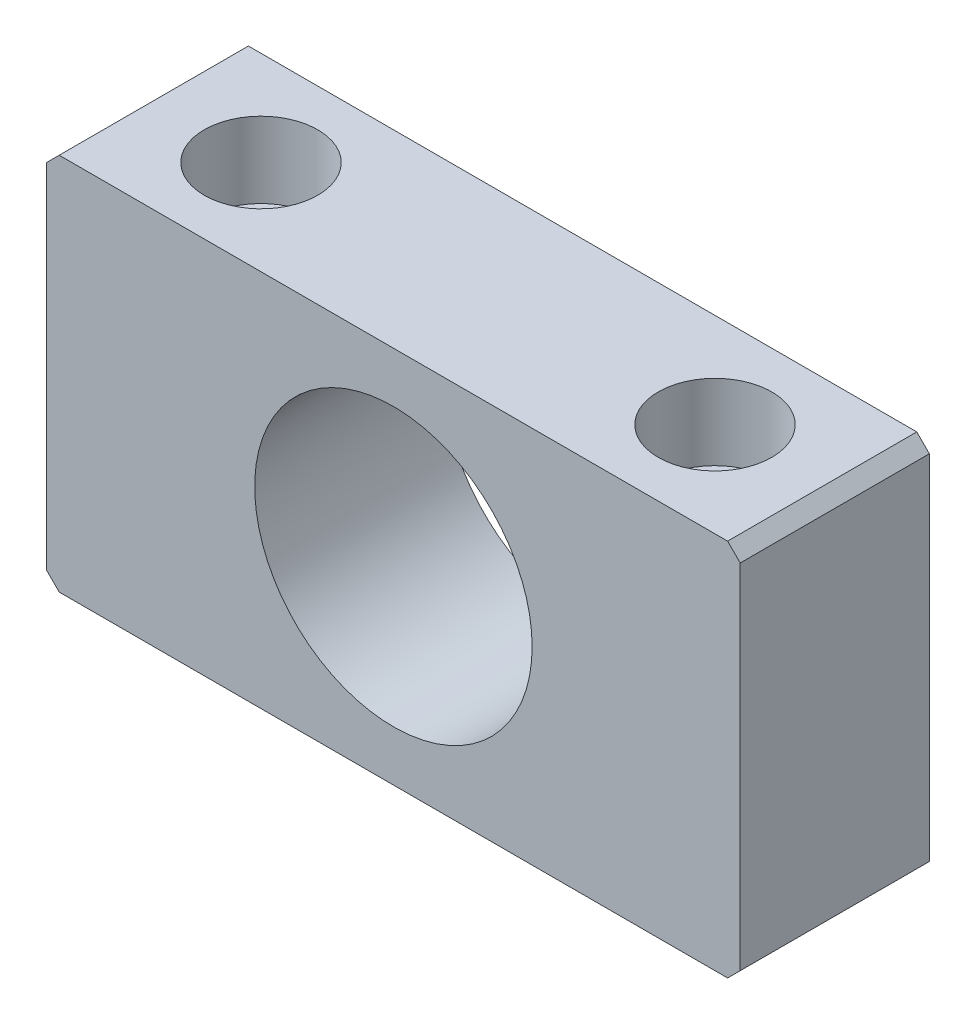
SolidWorks part; units mm, degrees
material "6061 合金"
ref_plane "前视基准面" through (0, 0, 0) normal (0, 0, 1) x (1, 0, 0)
ref_plane "上视基准面" through (0, 0, 0) normal (0, 1, 0) x (1, 0, 0)
ref_plane "右视基准面" through (0, 0, 0) normal (1, 0, 0) x (0, 0, -1)
sketch "草图1" plane through (0, 0, 0) normal (0, 0, 1) x (1, 0, 0)
  line L1 (-27.5, 15) -> (27.5, 15)
  line L2 (-27.5, 15) -> (-27.5, -15)
  line L3 (-27.5, -15) -> (27.5, -15)
  line L4 (27.5, 15) -> (27.5, -15)
  line L5 (0, -15) -> (0, 15) construction
  line L6 (-27.5, 0) -> (27.5, 0) construction
  circle A0 centre (0, 0) radius 11
  point P60 (0, 0)
  dimension "D1" = 22
  dimension "D2" = 15
  dimension "D3" = 55
  dimension "D4" = 30
extrude "凸台-拉伸1" add sketch "草图1" along normal blind 15
sketch "草图2" plane through (0, 15, 0) normal (0, 1, 0) x (1, 0, 0)
  line L0 (-27.5, -7.5) -> (27.5, -7.5) construction
  line L1 (-27.5, -15) -> (-27.5, 0) construction
  line L2 (27.5, -15) -> (27.5, 0) construction
  line L3 (0, 0) -> (0, -23.5605) construction
  circle A0 centre (-18, -7.5) radius 2.55
  circle A1 centre (18, -7.5) radius 2.55
  dimension "D1" = 36
  dimension "D2" = 5.1
extrude "切除-拉伸1" cut sketch "草图2" against normal through all
sketch "草图3" plane through (0, 15, 0) normal (0, 1, 0) x (1, 0, 0)
  circle A0 centre (-18, -7.5) radius 4.5
  circle A1 centre (18, -7.5) radius 4.5
  dimension "D1" = 9
extrude "切除-拉伸2" cut sketch "草图3" against normal blind 6
chamfer "倒角1" distance 1 angle 45 4 edges at (27.5, -15, 7.5) (-27.5, -15, 7.5) (-27.5, 15, 7.5) (27.5, 15, 7.5)
